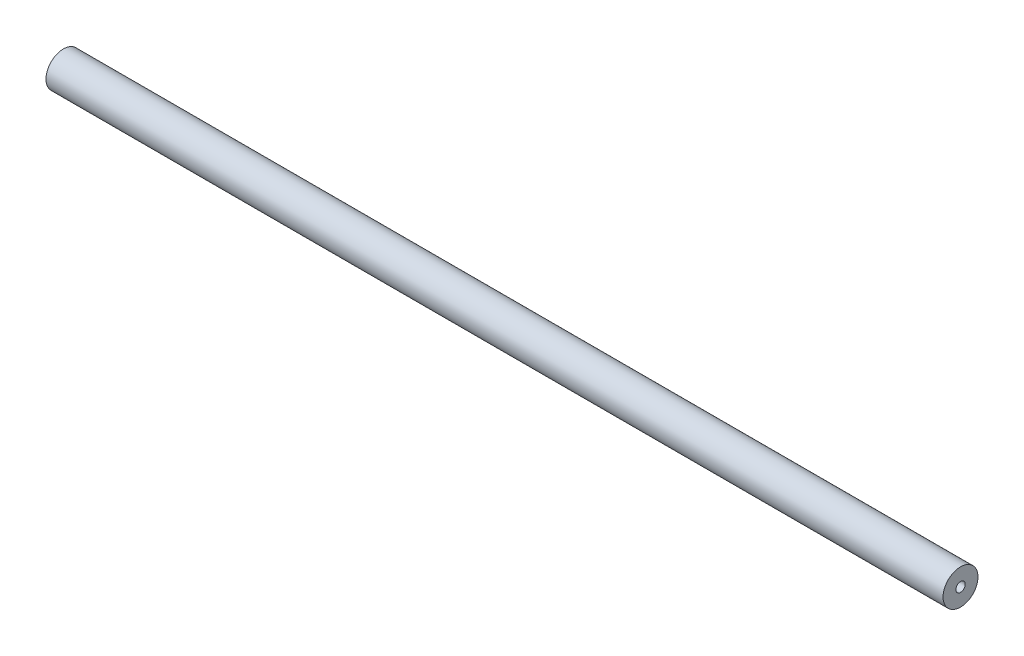
SolidWorks part; units mm, degrees
material "AISI 1045 Steel, cold drawn"
ref_plane "Front Plane" through (0, 0, 0) normal (0, 0, 1) x (1, 0, 0)
ref_plane "Top Plane" through (0, 0, 0) normal (0, 1, 0) x (1, 0, 0)
ref_plane "Right Plane" through (0, 0, 0) normal (1, 0, 0) x (0, 0, -1)
sketch "Sketch1" plane through (0, 0, 0) normal (1, 0, 0) x (0, 0, -1)
  circle A0 centre (0, 0) radius 9.525
  dimension "D1" = 19.05
extrude "Boss-Extrude1" add sketch "Sketch1" against normal blind 488.95
hole_wizard "1/4-20 Tapped Hole1" positions "Sketch3" profile "Sketch4" tap size "1/4-20" standard "ANSI Inch"
sketch "Sketch3" plane through (0, 0, 0) normal (1, 0, 0) x (0, 0, -1)
  point P0 (0, 0)
sketch "Sketch4" plane through (0, 0, 0) normal (0, 1, 0) x (0, 0, -1)
  line L0 (0, 0) -> (0, 18.0438)
  line L1 (0, 18.0438) -> (2.5527, 16.51)
  line L2 (2.5527, 16.51) -> (2.5527, 0)
  line L5 (2.5527, 0) -> (0, 0)
  line L10 (0, 18.0438) -> (-2.5527, 16.51) construction
  line L11 (0, -6.35) -> (0, 107.95) construction
  dimension "Tap Drill Dia." = 5.1054
  dimension "Tap Drill Depth" = 16.51
  dimension "Drill Angle" = 118
cosmetic thread "Hole Thread1" parameters "D1"=12.7, "D2"=6.35
hole_wizard "1/4-20 Tapped Hole2" positions "Sketch5" profile "Sketch6" tap size "1/4-20" standard "ANSI Inch"
sketch "Sketch5" plane through (-488.95, 0, 0) normal (-1, 0, 0) x (0, 0, 1)
  point P0 (0, 0)
sketch "Sketch6" plane through (-488.95, 0, 0) normal (0, 1, 0) x (0, 0, 1)
  line L0 (0, 0) -> (0, 18.0438)
  line L1 (0, 18.0438) -> (2.5527, 16.51)
  line L2 (2.5527, 16.51) -> (2.5527, 0)
  line L5 (2.5527, 0) -> (0, 0)
  line L10 (0, 18.0438) -> (-2.5527, 16.51) construction
  line L11 (0, -6.35) -> (0, 107.95) construction
  dimension "Tap Drill Dia." = 5.1054
  dimension "Tap Drill Depth" = 16.51
  dimension "Drill Angle" = 118
cosmetic thread "Hole Thread2" parameters "D1"=12.7, "D2"=6.35
